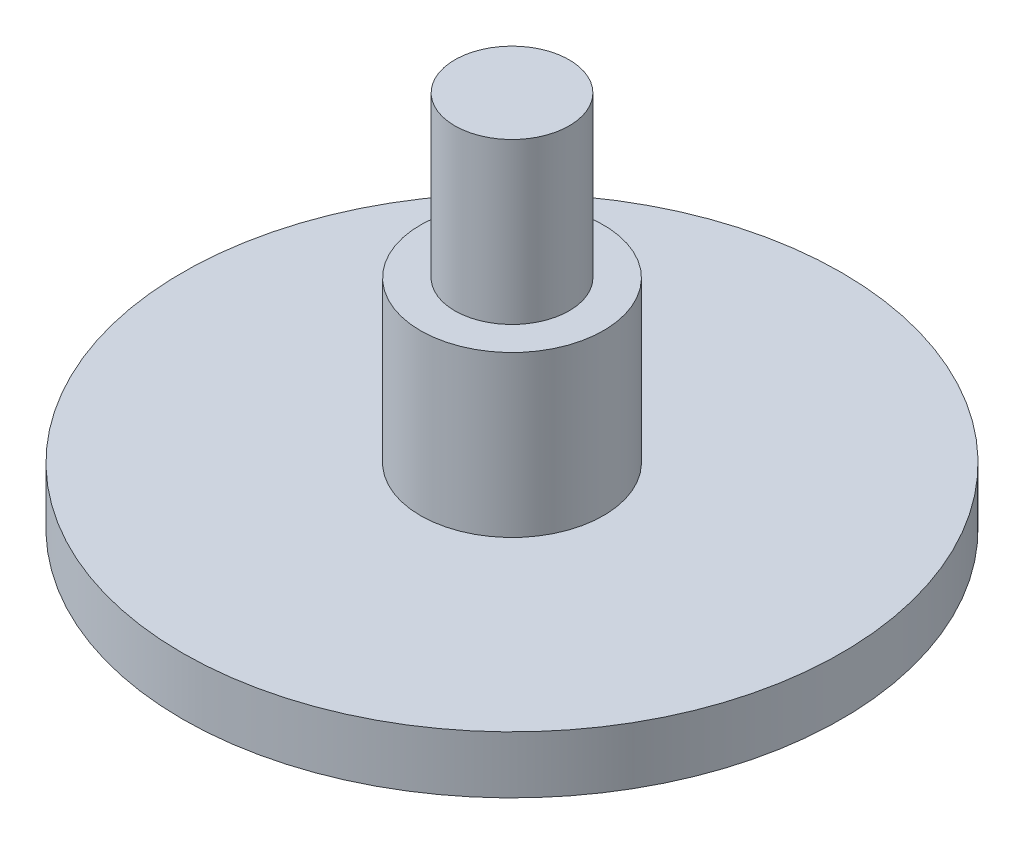
SolidWorks part; units mm, degrees
ref_plane "Front Plane" through (0, 0, 0) normal (0, 0, 1) x (1, 0, 0)
ref_plane "Top Plane" through (0, 0, 0) normal (0, 1, 0) x (1, 0, 0)
ref_plane "Right Plane" through (0, 0, 0) normal (1, 0, 0) x (0, 0, -1)
sketch "Sketch1" plane through (0, 0, 0) normal (0, 1, 0) x (1, 0, 0)
  circle A0 centre (0, 0) radius 28.8
  dimension "D1" = 57.6
extrude "Boss-Extrude1" add sketch "Sketch1" along normal blind 5
sketch "Sketch2" plane through (0, 5, 0) normal (0, 1, 0) x (1, 0, 0)
  circle A0 centre (0, 0) radius 8
  dimension "D1" = 16
extrude "Boss-Extrude2" add sketch "Sketch2" along normal blind 14
sketch "Sketch3" plane through (0, 19, 0) normal (0, 1, 0) x (1, 0, 0)
  circle A0 centre (0, 0) radius 5
  dimension "D1" = 10
extrude "Boss-Extrude3" add sketch "Sketch3" along normal blind 14
